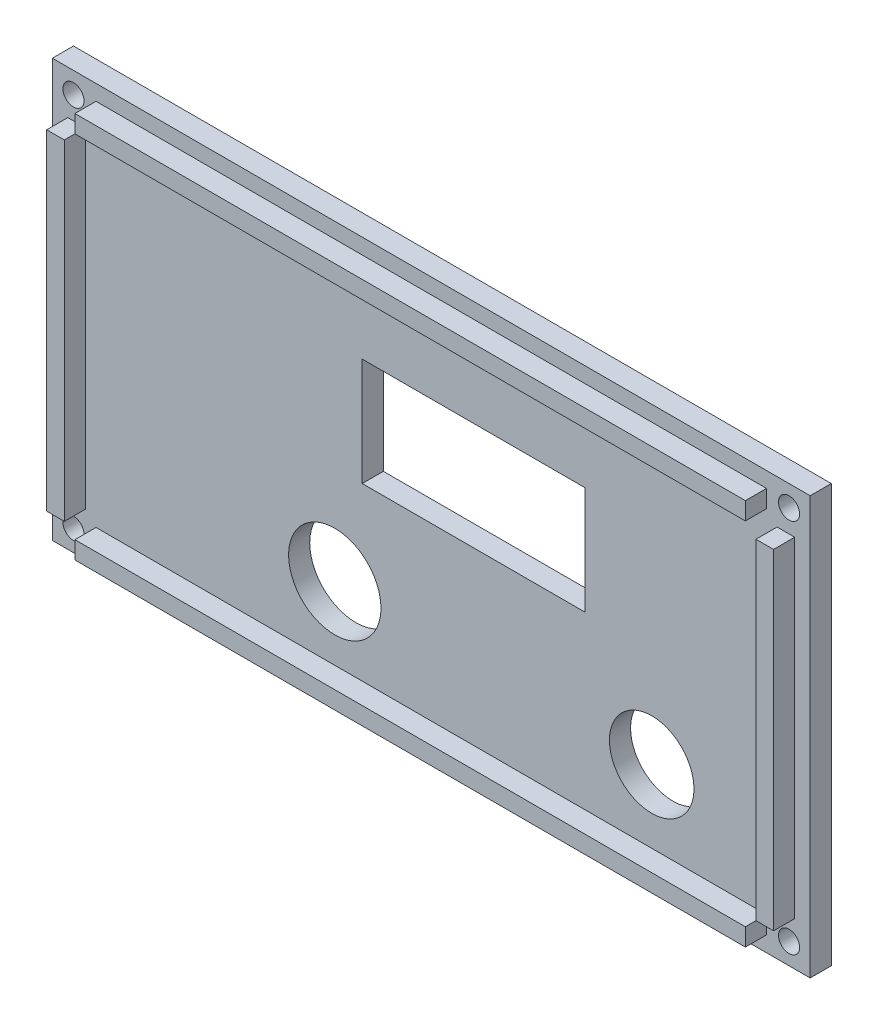
SolidWorks part; units mm, degrees
ref_plane "Front Plane" through (0, 0, 0) normal (0, 0, 1) x (1, 0, 0)
ref_plane "Top Plane" through (0, 0, 0) normal (0, 1, 0) x (1, 0, 0)
ref_plane "Right Plane" through (0, 0, 0) normal (1, 0, 0) x (0, 0, -1)
sketch "Sketch1" plane through (0, 0, 0) normal (0, 0, 1) x (1, 0, 0)
  line L1 (0, 0) -> (107.6, 0)
  line L2 (0, 0) -> (0, 59.3)
  line L3 (0, 59.3) -> (107.6, 59.3)
  line L4 (107.6, 0) -> (107.6, 59.3)
  dimension "D1" = 107.6
  dimension "D2" = 59.3
extrude "Boss-Extrude1" add sketch "Sketch1" along normal blind 3
sketch "Sketch2" plane through (0, 0, 3) normal (0, 0, 1) x (1, 0, 0)
  line L0 (107.6, 59.3) -> (0, 59.3) construction
  line L1 (6.2, 57.1) -> (101.4, 57.1)
  line L2 (6.2, 57.1) -> (6.2, 54.6)
  line L3 (6.2, 54.6) -> (101.4, 54.6)
  line L4 (101.4, 57.1) -> (101.4, 54.6)
  line L5 (2.2, 53.1) -> (4.7, 53.1)
  line L6 (2.2, 53.1) -> (2.2, 6.2)
  line L7 (2.2, 6.2) -> (4.7, 6.2)
  line L8 (4.7, 53.1) -> (4.7, 6.2)
  line L9 (6.2, 4.7) -> (101.4, 4.7)
  line L10 (6.2, 4.7) -> (6.2, 2.2)
  line L11 (6.2, 2.2) -> (101.4, 2.2)
  line L12 (101.4, 4.7) -> (101.4, 2.2)
  line L13 (105.4, 53.1) -> (102.9, 53.1)
  line L14 (105.4, 53.1) -> (105.4, 6.2)
  line L15 (105.4, 6.2) -> (102.9, 6.2)
  line L16 (102.9, 53.1) -> (102.9, 6.2)
  line L17 (0, 59.3) -> (0, 0) construction
  line L18 (0, 0) -> (107.6, 0) construction
  line L19 (107.6, 0) -> (107.6, 59.3) construction
  dimension "D1" = 2.2
  dimension "D2" = 2.2
  dimension "D3" = 2.2
  dimension "D4" = 2.2
  dimension "D5" = 2.5
  dimension "D6" = 2.5
  dimension "D7" = 2.5
  dimension "D8" = 2.5
  dimension "D9" = 6.2
  dimension "D10" = 6.2
  dimension "D11" = 6.2
  dimension "D12" = 6.2
  dimension "D13" = 6.2
  dimension "D14" = 6.2
  dimension "D15" = 6.2
  dimension "D16" = 6.2
extrude "Boss-Extrude2" add sketch "Sketch2" along normal blind 3
sketch "Sketch3" plane through (0, 0, 0) normal (0, 0, -1) x (-1, 0, 0)
  line L0 (-107.6, 0) -> (-107.6, 59.3) construction
  line L1 (-107.6, 59.3) -> (0, 59.3) construction
  line L2 (0, 0) -> (-107.6, 0) construction
  line L3 (-75.6, 44.3) -> (-44, 44.3)
  line L4 (-75.6, 44.3) -> (-75.6, 29)
  line L5 (-75.6, 29) -> (-44, 29)
  line L6 (-44, 44.3) -> (-44, 29)
  line L7 (0, 59.3) -> (0, 0) construction
  circle A0 centre (-104.6, 56.3) radius 1.5
  circle A1 centre (-3, 56.3) radius 1.5
  circle A2 centre (-3, 3) radius 1.5
  circle A3 centre (-104.6, 3) radius 1.5
  circle A4 centre (-85.1, 15) radius 6
  circle A5 centre (-40.1, 15) radius 6.5576
  dimension "D1" = 3
  dimension "D2" = 3
  dimension "D3" = 3
  dimension "D10" = 15
  dimension "D11" = 22.5
  dimension "D12" = 12
  dimension "D13" = 15
  dimension "D6" = 29
  dimension "D7" = 32
  dimension "D8" = 15
  dimension "D9" = 44
  dimension "45" = 45
  dimension "D4" = 2
  dimension "D5" = 2
extrude "Cut-Extrude1" cut sketch "Sketch3" against normal blind 5
